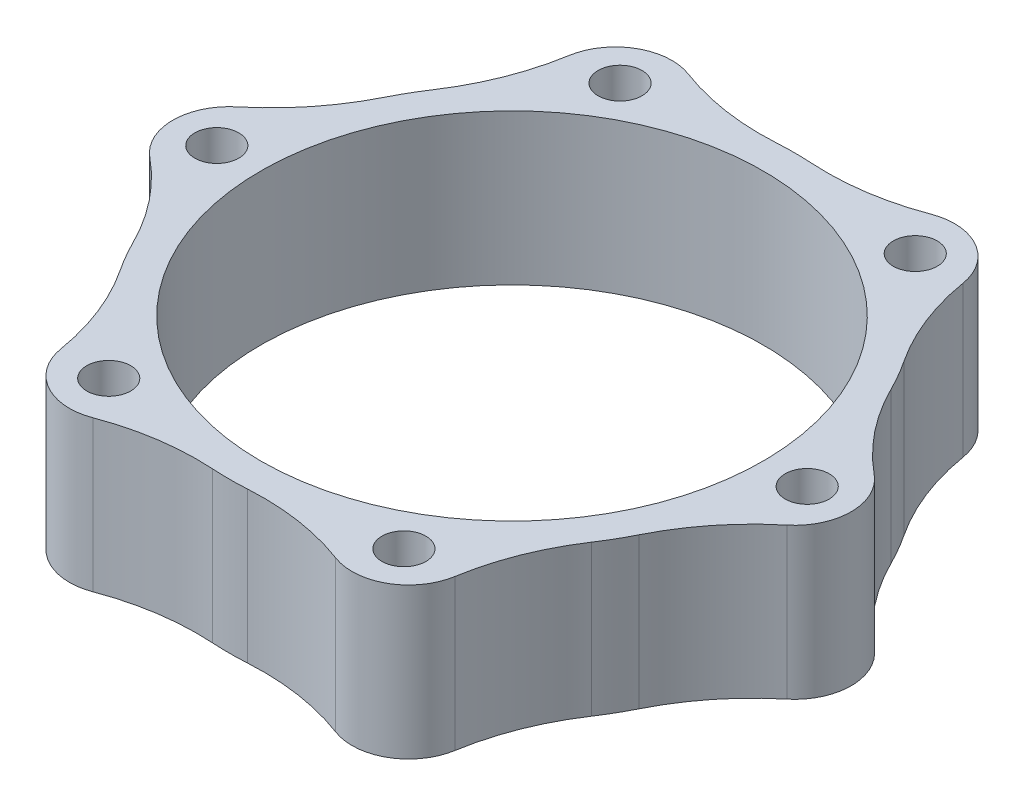
SolidWorks part; units mm, degrees
ref_plane "Front Plane" through (0, 0, 0) normal (0, 0, 1) x (1, 0, 0)
ref_plane "Top Plane" through (0, 0, 0) normal (0, 1, 0) x (1, 0, 0)
ref_plane "Right Plane" through (0, 0, 0) normal (1, 0, 0) x (0, 0, -1)
sketch "Sketch1" plane through (0, 0, 0) normal (0, 1, 0) x (1, 0, 0)
  circle A0 centre (0, 0) radius 28.575
  circle A1 centre (0, 0) radius 25.4
  circle A3 centre (0, 0) radius 25.4 construction
  dimension "D1" = 3.175
extrude "Boss-Extrude1" add sketch "Sketch1" along normal up to surface (15.24 mm away)
sketch "Sketch2" plane through (0, 15.24, 0) normal (0, 1, 0) x (1, 0, 0)
  line L0 (0, 0) -> (-28.575, 0) construction
  arc A0 (-28.0035, 5.6864) -> (-28.0035, -5.6864) centre (-28.575, 0) ccw
  circle A1 centre (0, 0) radius 28.575 construction
  arc A4 (-28.0035, 5.6864) -> (-28.0035, -5.6864) centre (0, 0) ccw
  dimension "D1" = 11.43
extrude "Boss-Extrude2" add sketch "Sketch2" against normal up to surface (15.24 mm away) contours A0 A4 up to face at (0, 0, 28.575)
fillet "Fillet1" radius 25.4 2 edges at (-28.0035, 7.62, -5.6864) (-28.0035, 7.62, 5.6864)
pattern_circular "CirPattern1" count 6 over 360 about axis through (0, 0, 0) along (0, 1, 0) of "Boss-Extrude2", "Fillet1"
sketch "Sketch3" plane through (0, 15.24, 0) normal (0, 1, 0) x (1, 0, 0)
  line L0 (-34.29, 0) -> (-25.4, 0) construction
  circle A0 centre (-29.845, 0) radius 2.2225
  arc A1 (-32.2023, 4.4163) -> (-32.2023, -4.4163) centre (-28.575, 0) ccw construction
  circle A2 centre (0, 0) radius 25.4 construction
  dimension "D1" = 4.445
extrude "Cut-Extrude1" cut sketch "Sketch3" against normal through all both and the other way through all
pattern_circular "CirPattern2" count 6 over 360 about axis through (0, 0, 0) along (0, 1, 0) of "Cut-Extrude1"
